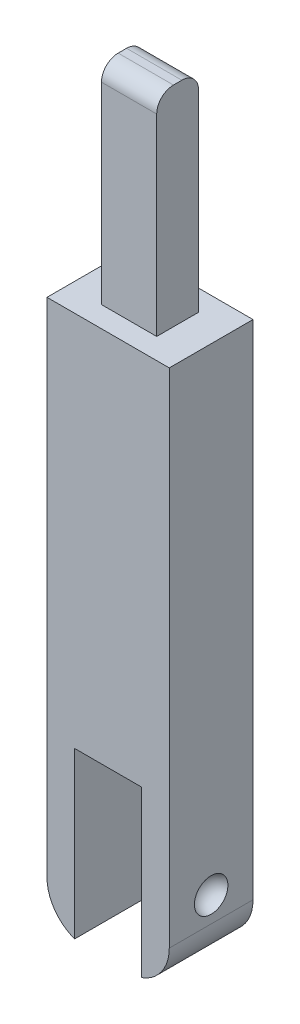
SolidWorks part; units mm, degrees
ref_plane "Front Plane" through (0, 0, 0) normal (0, 0, 1) x (1, 0, 0)
ref_plane "Top Plane" through (0, 0, 0) normal (0, 1, 0) x (1, 0, 0)
ref_plane "Right Plane" through (0, 0, 0) normal (1, 0, 0) x (0, 0, -1)
sketch "Sketch1" plane through (0, 0, 0) normal (0, 0, 1) x (1, 0, 0)
  line L3 (-7.3, 50) -> (7.3, 50)
  line L4 (-7.3, 50) -> (-7.3, -40)
  line L5 (-7.3, -40) -> (7.3, -40)
  line L6 (7.3, 50) -> (7.3, -40)
  dimension "D1" = 90
  dimension "D2" = 14.6
  dimension "D3" = 7.3
  dimension "D4" = 40
extrude "Boss-Extrude1" add sketch "Sketch1" along normal mid plane 10
fillet "Fillet1" radius 5 2 edges at (-7.3, -40, 0) (7.3, -40, 0)
sketch "Sketch4" plane through (0, 0, 0) normal (0, 0, 1) x (1, 0, 0)
  line L0 (-17.6663, -32) -> (24.9562, -32) construction
  line L1 (-2.3, -40) -> (2.3, -40) construction
  line L2 (-7.3, -32) -> (-5.3, -32)
  line L3 (-7.3, 50) -> (-7.3, -35) construction
  line L4 (-7.3, -30) -> (-7.3, -32)
  line L5 (7.3, -32) -> (5.3, -32)
  line L6 (7.3, -35) -> (7.3, 50) construction
  line L7 (7.3, -30) -> (7.3, -32)
  arc A0 (-5.3, -32) -> (-7.3, -30) centre (-7.3, -32) ccw
  arc A1 (5.3, -32) -> (7.3, -30) centre (7.3, -32) cw
  dimension "D1" = 8
  dimension "D2" = 2
  dimension "D3" = 2
revolve "Cut-Revolve2" cut sketch "Sketch4" angle 360 about L0
sketch "Sketch6" plane through (0, 0, 5) normal (0, 0, 1) x (1, 0, 0)
  line L0 (-7.3, 50) -> (-7.3, -25)
  line L1 (-7.3, 50) -> (-7.3, -35) construction
  line L2 (-7.3, 25) -> (-3.3, 25)
  line L3 (-3.3, 25) -> (-3.3, 50)
  line L4 (7.3, 50) -> (-7.3, 50) construction
  line L5 (-3.3, 50) -> (-7.3, 50)
  line L6 (7.3, 50) -> (7.3, -25)
  line L7 (7.3, -35) -> (7.3, 50) construction
  line L8 (7.3, 50) -> (3.3, 50)
  line L9 (3.3, 50) -> (3.3, 25)
  line L10 (3.3, 25) -> (7.3, 25)
  line M6 (-7.3, 50) -> (-7.3, -35)
  line M11 (7.3, 50) -> (-7.3, 50)
  dimension "D1" = 75
  dimension "D2" = 4
  dimension "D3" = 25
  dimension "D4" = 25
  dimension "D5" = 4
extrude "Cut-Extrude1" cut sketch "Sketch6" against normal through all contours L2 L3 M11 M6 | L9 L10 L6 M11
sketch "Sketch7" plane through (3.3, 0, 0) normal (1, 0, 0) x (0, 0, -1)
  line L0 (-5, 25) -> (-2.5, 25)
  line L1 (5, 25) -> (-5, 25) construction
  line L2 (-2.5, 25) -> (-2.5, 50)
  line L3 (5, 50) -> (-5, 50) construction
  line L4 (-2.5, 50) -> (-5, 50)
  line L5 (-5, 50) -> (-5, 25)
  line L6 (5, 25) -> (2.5, 25)
  line L7 (5, 25) -> (-5, 25) construction
  line L8 (2.5, 25) -> (2.5, 50)
  line L9 (2.5, 50) -> (5, 50)
  line L10 (5, 50) -> (5, 25)
  dimension "D1" = 2.5
  dimension "D2" = 2.5
extrude "Cut-Extrude2" cut sketch "Sketch7" against normal through all
fillet "Fillet4" radius 2 2 edges at (0, 50, -2.5) (0, 50, 2.5)
sketch "Sketch8" plane through (0, 0, -5) normal (0, 0, -1) x (-1, 0, 0)
  line L1 (-4, -20) -> (4, -20)
  line L2 (-4, -20) -> (-4, -40)
  line L3 (-4, -40) -> (4, -40)
  line L4 (4, -20) -> (4, -40)
  line L5 (2.3, -40) -> (-2.3, -40) construction
  line L6 (7.3, 25) -> (7.3, -35) construction
  dimension "D1" = 8
  dimension "D2" = 3.3
  dimension "D3" = 20
extrude "Cut-Extrude3" cut sketch "Sketch8" against normal through all
